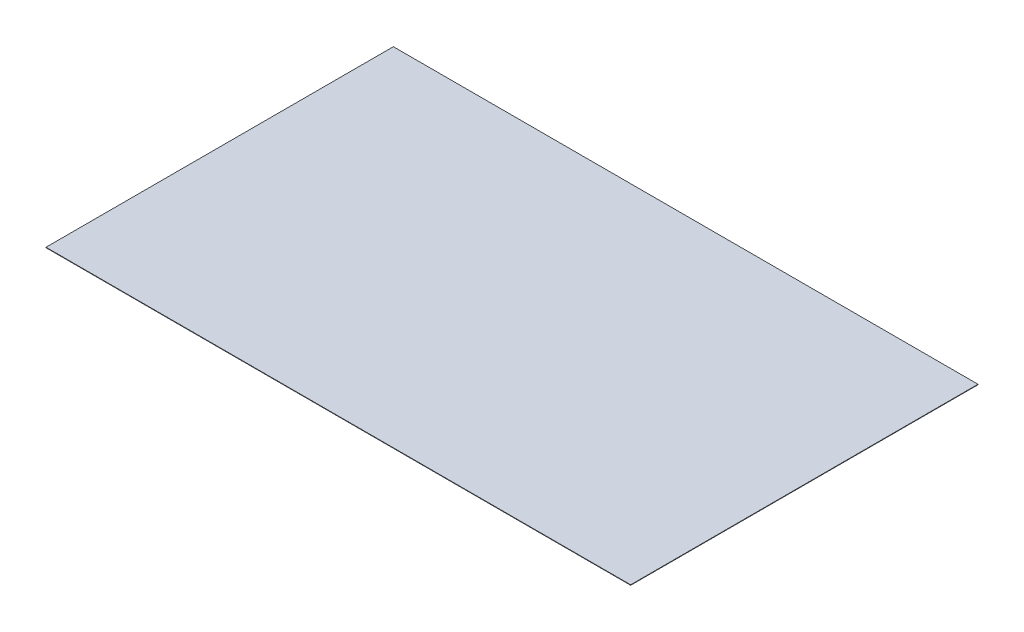
SolidWorks part; units mm, degrees
ref_plane "Front Plane" through (0, 0, 0) normal (0, 0, 1) x (1, 0, 0)
ref_plane "Top Plane" through (0, 0, 0) normal (0, 1, 0) x (1, 0, 0)
ref_plane "Right Plane" through (0, 0, 0) normal (1, 0, 0) x (0, 0, -1)
other "Configuration Table"
sketch "Sketch1" plane through (0, 0, 0) normal (0, 0, 1) x (1, 0, 0)
  line L1 (62.5, 181.5) -> (1337.5, 181.5)
  line L2 (62.5, 181.5) -> (62.5, 182.5)
  line L3 (62.5, 182.5) -> (1337.5, 182.5)
  line L4 (1337.5, 181.5) -> (1337.5, 182.5)
extrude "STORE_ic_alt_1" add sketch "Sketch1" against normal blind 757.5 separate body
